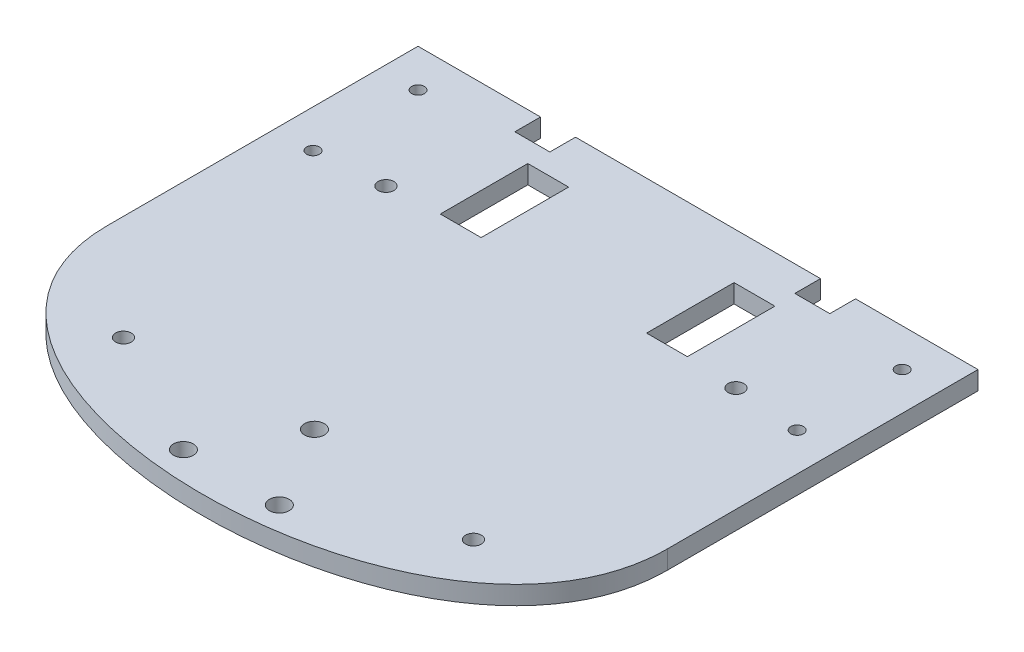
SolidWorks part; units mm, degrees
ref_plane "Front Plane" through (0, 0, 0) normal (0, 0, 1) x (1, 0, 0)
ref_plane "Top Plane" through (0, 0, 0) normal (0, 1, 0) x (1, 0, 0)
ref_plane "Right Plane" through (0, 0, 0) normal (1, 0, 0) x (0, 0, -1)
sketch "Sketch2" plane through (0, 0, 0) normal (0, 1, 0) x (1, 0, 0)
  line L4 (-48, -33.6908) -> (-48, 91.0268) construction
  line L5 (48, -42.5) -> (-48, -42.5) construction
  line L6 (48, -42.5) -> (48, 42.5) construction
  line L7 (48, 42.5) -> (-48, 42.5)
  line L8 (-48, -42.5) -> (-48, 42.5) construction
  line L9 (48, -42.5) -> (-48, 42.5) construction
  line L10 (48, 42.5) -> (-48, -42.5) construction
  line L11 (48, 148.5724) -> (48, -105.4276) construction
  line L12 (-48, 42.5) -> (-48, -10.75)
  line L13 (48, 42.5) -> (48, -10.75)
  spline S0 degree 3 poles (-48, -10.75) (-48, -53.0833) (48, -53.0833) (48, -10.75) knots 0 0 0 0 1 1 1 1
  point P0 (0, 0)
  dimension "D3" = 180
  dimension "D4" = 127
  dimension "D5" = 85
  dimension "D1" = 96
  dimension "D2" = 180
  dimension "D6" = 127
extrude "Boss-Extrude1" add sketch "Sketch2" along normal blind 3.175
sketch "Sketch3" plane through (0, 3.175, 0) normal (0, 1, 0) x (1, 0, 0)
  line L0 (0, 0) -> (0, 15) construction
  line L10 (48, 42.5) -> (-48, 42.5) construction
  line L11 (-41.5, 36) -> (-41.5, 18) construction
  line L12 (41.5, 36) -> (41.5, 18) construction
  line L13 (-30, 19) -> (-30, -26) construction
  line L14 (30, 19) -> (30, -26) construction
  line L15 (0, -42.5) -> (28.6945, -42.5) construction
  line L16 (-21.18, 34.5) -> (-14.18, 34.5)
  line L17 (-21.18, 34.5) -> (-21.18, 19.5)
  line L18 (-21.18, 19.5) -> (-14.18, 19.5)
  line L19 (-14.18, 34.5) -> (-14.18, 19.5)
  line L20 (-48, 42.5) -> (-48, -10.75) construction
  line L24 (14.18, 34.5) -> (21.18, 34.5)
  line L25 (14.18, 34.5) -> (14.18, 19.5)
  line L26 (14.18, 19.5) -> (21.18, 19.5)
  line L27 (21.18, 34.5) -> (21.18, 19.5)
  circle A0 centre (-41.5, 36) radius 1.0922
  circle A1 centre (-41.5, 18) radius 1.0922
  circle A2 centre (-30, 19) radius 1.35
  circle A3 centre (41.5, 18) radius 1.0922
  circle A4 centre (41.5, 36) radius 1.0922
  circle A5 centre (-30, -26) radius 1.35
  circle A6 centre (30, -26) radius 1.35
  circle A7 centre (30, 19) radius 1.35
  circle A8 centre (-8.225, -37.5) radius 1.7
  circle A9 centre (8.225, -37.5) radius 1.7
  circle A10 centre (0, -23.2539) radius 1.7
  spline S1 degree 3 poles (-48, -10.75) (-48, -53.0833) (48, -53.0833) (48, -10.75) knots 0 0 0 0 1 1 1 1 construction
  dimension "D5" = 2.1844
  dimension "D6" = 2.1844
  dimension "D9" = 2.7
  dimension "D13" = 3.4
  dimension "D2" = 6.5
  dimension "D3" = 1.5
  dimension "D4" = 7
  dimension "D7" = 18
  dimension "D8" = 16.45
  dimension "D10" = 23.5
  dimension "D11" = 30
  dimension "D12" = 45
  dimension "D14" = 20.32
  dimension "D15" = 15
  dimension "D16" = 16.45
  dimension "D17" = 16.45
  dimension "D18" = 8
  dimension "D19" = 5
extrude "Cut-Extrude1" cut sketch "Sketch3" against normal through all and the other way through all
sketch "Sketch5" plane through (0, 3.175, 0) normal (0, 1, 0) x (1, 0, 0)
  line L0 (0, -0.2815) -> (0, 85.2815) construction
  line L1 (48, 42.5) -> (-48, 42.5) construction
  line L10 (21, 42.5) -> (27, 42.5)
  line L11 (21, 42.5) -> (21, 38.1)
  line L12 (21, 38.1) -> (27, 38.1)
  line L13 (27, 42.5) -> (27, 38.1)
  line L18 (-27, 42.5) -> (-21, 42.5)
  line L19 (-27, 42.5) -> (-27, 38.1)
  line L20 (-27, 38.1) -> (-21, 38.1)
  line L21 (-21, 42.5) -> (-21, 38.1)
  point P2 (-24, 38.1)
  dimension "D1" = 6
  dimension "D2" = 4.4
  dimension "D3" = 6
  dimension "D4" = 4.4
extrude "Cut-Extrude2" cut sketch "Sketch5" against normal through all
